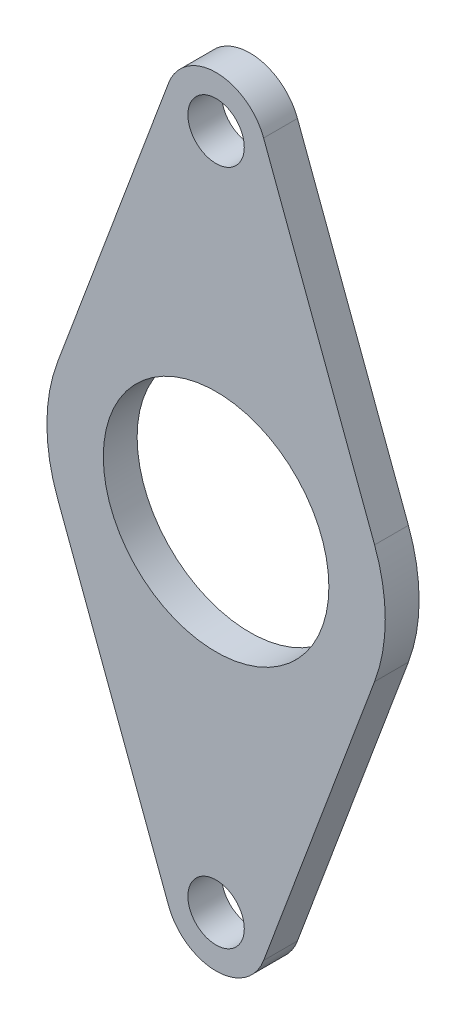
SolidWorks part; units mm, degrees
ref_plane "前视基准面" through (0, 0, 0) normal (0, 0, 1) x (1, 0, 0)
ref_plane "上视基准面" through (0, 0, 0) normal (0, 1, 0) x (1, 0, 0)
ref_plane "右视基准面" through (0, 0, 0) normal (1, 0, 0) x (0, 0, -1)
other "Configuration Table"
sketch "草图1" plane through (0, 0, 0) normal (0, 0, 1) x (1, 0, 0)
  line L0 (-45.532, 0) -> (26.493, 0) construction
  line L1 (0, 35.4691) -> (0, -35.0292) construction
  line L2 (-4.2154, 31.575) -> (-14.0512, 5.25)
  line L3 (4.2154, 31.575) -> (14.0512, 5.25)
  line L4 (-4.2154, -31.575) -> (-14.0512, -5.25)
  line L5 (4.2154, -31.575) -> (14.0512, -5.25)
  arc A0 (-14.0512, 5.25) -> (-14.0512, -5.25) centre (0, 0) ccw
  arc A1 (4.2154, 31.575) -> (-4.2154, 31.575) centre (0, 30) ccw
  arc A2 (-4.2154, -31.575) -> (4.2154, -31.575) centre (0, -30) ccw
  circle A3 centre (0, 30) radius 2.5
  circle A4 centre (0, -30) radius 2.5
  circle A5 centre (0, 0) radius 10
  arc A6 (14.0512, -5.25) -> (14.0512, 5.25) centre (0, 0) ccw
  point P18 (2.2986, -33.8687)
  dimension "D2" = 5
  dimension "D3" = 9
  dimension "D4" = 30
  dimension "D5" = 20
  dimension "D1" = 30
extrude "凸台-拉伸1" add sketch "草图1" along normal blind 3
